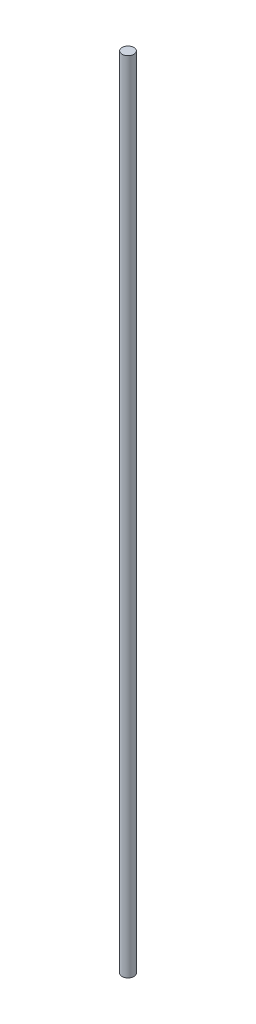
SolidWorks part; units mm, degrees
ref_plane "Front Plane" through (0, 0, 0) normal (0, 0, 1) x (1, 0, 0)
ref_plane "Top Plane" through (0, 0, 0) normal (0, 1, 0) x (1, 0, 0)
ref_plane "Right Plane" through (0, 0, 0) normal (1, 0, 0) x (0, 0, -1)
sketch "Sketch1" plane through (0, 0, 0) normal (0, 1, 0) x (1, 0, 0)
  circle A0 centre (0, 0) radius 1
  dimension "D1" = 2
extrude "Boss-Extrude1" add sketch "Sketch1" along normal blind 135
